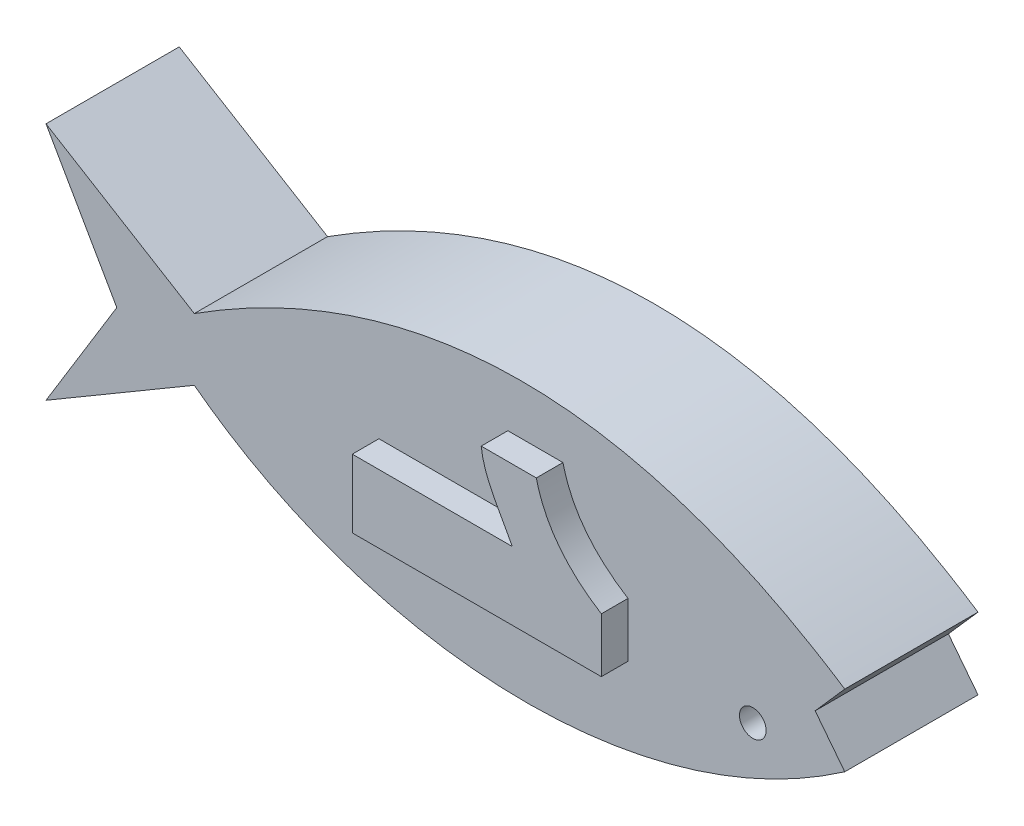
SolidWorks part; units mm, degrees
ref_plane "Front" through (0, 0, 0) normal (0, 0, 1) x (1, 0, 0)
ref_plane "Top" through (0, 0, 0) normal (0, 1, 0) x (1, 0, 0)
ref_plane "Right" through (0, 0, 0) normal (1, 0, 0) x (0, 0, -1)
sketch "Sketch2" plane through (0, 0, 0) normal (0, 0, -1) x (1, 0, 0)
  line L0 (29.973, 6.6427) -> (28.8624, 5.2157)
  line L1 (28.8624, 5.2157) -> (29.973, 3.9538)
  line L2 (5.5653, 6.2857) -> (0, 9.5561)
  line L3 (0, 9.5561) -> (2.6565, 5.2157)
  line L4 (2.6565, 5.2157) -> (0, 0.5701)
  line L5 (0, 0.5701) -> (5.5653, 3.9538)
  circle A0 centre (26.5226, 6.7807) radius 0.5001
  spline S0 degree 3 poles (5.5653, 6.2857) (12.0373, 11.2173) (22.1418, 12.0787) (29.973, 6.6427) knots 0 0 0 0 1 1 1 1
  spline S1 degree 2 poles (5.5653, 3.9538) (17.9191, -3.9397) (29.973, 3.9538) knots 0 0 0 1 1 1
extrude "Boss-Extrude1" add sketch "Sketch2" against normal blind 5
ref_plane "Fish Top Plane" through (0, 0, 5) normal (0, 0, 1) x (-1, 0, 0)
sketch "Sketch4" plane through (0, 0, 5) normal (0, 0, 1) x (-1, 0, 0)
  line L0 (-17.3307, 1.8791) -> (-19.3982, 1.8791)
  line L1 (-21.8386, 5.0752) -> (-21.8386, 7.1183)
  line L2 (-21.8386, 7.1183) -> (-12.4933, 7.1183)
  line L3 (-12.4933, 7.1183) -> (-12.4933, 4.5593)
  line L4 (-12.4933, 4.5593) -> (-18.4991, 4.5593)
  line L5 (8.5748, 11.2377) -> (8.5748, -5.2188) construction
  line L6 (8.5748, -5.2188) -> (8.7446, -5.1226) construction
  line L7 (8.7446, -5.1226) -> (28.8603, -5.1226) construction
  spline S0 degree 3 poles (-18.4991, 4.5593) (-18.0409, 3.6598) (-17.4434, 2.8803) (-17.3307, 1.8791) knots 0 0 0 0 1 1 1 1
  spline S1 degree 2 poles (-19.3982, 1.8791) (-19.8579, 3.8365) (-21.8386, 5.0752) knots 0 0 0 1 1 1
extrude "Boss-Extrude2" add sketch "Sketch4" along normal blind 1
